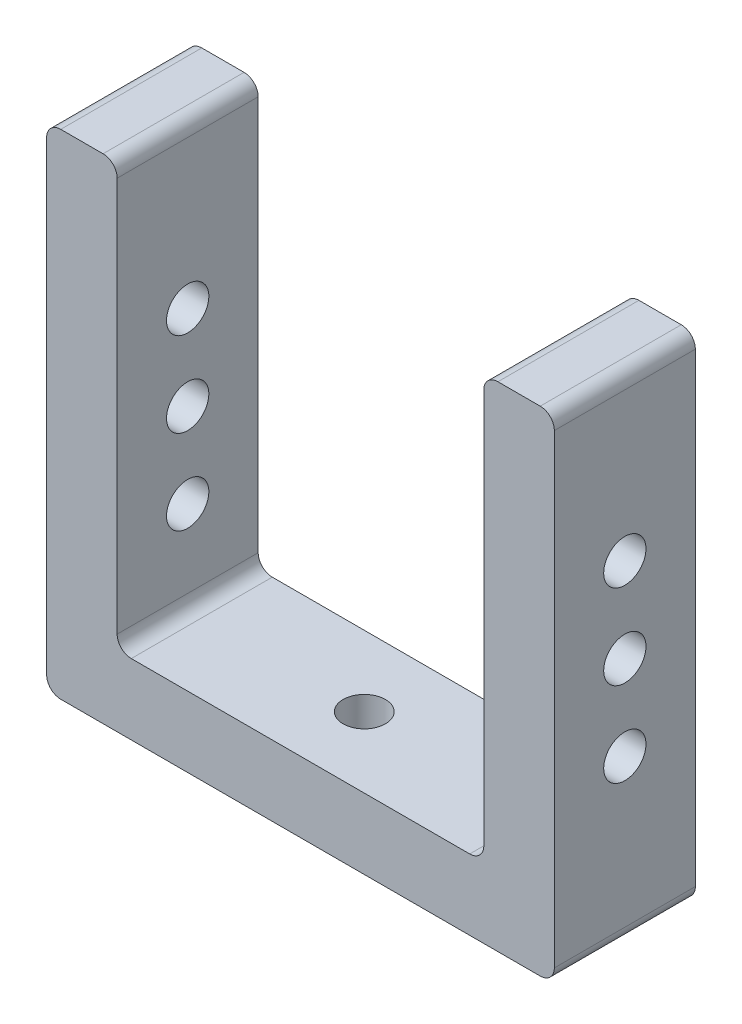
SolidWorks part; units mm, degrees
ref_plane "前视基准面" through (0, 0, 0) normal (0, 0, 1) x (1, 0, 0)
ref_plane "上视基准面" through (0, 0, 0) normal (0, 1, 0) x (1, 0, 0)
ref_plane "右视基准面" through (0, 0, 0) normal (1, 0, 0) x (0, 0, -1)
other "Configuration Table"
sketch "草图1" plane through (0, 0, 0) normal (0, 0, 1) x (1, 0, 0)
  line L0 (-17.0463, 30) -> (-12.0463, 30)
  line L1 (-12.0463, 30) -> (-12.0463, 1)
  line L2 (-11.0463, 0) -> (12.9537, 0)
  line L3 (13.9537, 1) -> (13.9537, 30)
  line L4 (13.9537, 30) -> (18.9537, 30)
  line L5 (18.9537, 30) -> (18.9537, -4)
  line L6 (12.9537, 0) -> (12.9537, -2)
  line L7 (17.9537, -5) -> (-16.0463, -5)
  line L8 (-17.0463, -4) -> (-17.0463, 30)
  arc A0 (18.9537, -4) -> (17.9537, -5) centre (17.9537, -4) cw
  arc A1 (12.9537, 0) -> (13.9537, 1) centre (12.9537, 1) ccw
  arc A2 (-16.0463, -5) -> (-17.0463, -4) centre (-16.0463, -4) cw
  arc A3 (-12.0463, 1) -> (-11.0463, 0) centre (-11.0463, 1) ccw
  point P17 (13.9537, 0)
  point P20 (-17.0463, -5)
  point P23 (-12.0463, 0)
  dimension "D1" = 1
  dimension "D2" = 26
  dimension "D3" = 5
  dimension "D4" = 35
  dimension "D5" = 30
  dimension "D6" = 30
  dimension "D7" = 5
extrude "凸台-拉伸1" add sketch "草图1" along normal blind 10 contours L8 L0 L1 A3 L2 A1 L3 L4 L5 A0 L7 A2
fillet "圆角1" radius 1 4 edges at (18.9537, 30, 5) (13.9537, 30, 5) (-17.0463, 30, 5) (-12.0463, 30, 5)
sketch "草图2" plane through (-17.0463, 0, 0) normal (-1, 0, 0) x (0, 0, 1)
  line L0 (0, 29) -> (0, -4) construction
  line L1 (0, 12.5) -> (10, 12.5) construction
  line L2 (10, -4) -> (10, 29) construction
  line L3 (5, 13) -> (5, -49987) construction
  circle A0 centre (5, 12.5) radius 1.5
  circle A1 centre (5, 6.5) radius 1.5
  circle A2 centre (5, 18.5) radius 1.5
  point P4 (0, 12.5)
  point P9 (5, 12.5)
  dimension "D1" = 3
  dimension "D2" = 2
  dimension "D3" = 2
sketch "草图3" plane through (0, -5, 0) normal (0, -1, 0) x (1, 0, 0)
  line L0 (0, 0) -> (0.9537, 10) construction
  line L1 (17.9537, 10) -> (-16.0463, 10) construction
  circle A0 centre (0.4768, 5) radius 1.5
  point P5 (0.4768, 5)
  dimension "D1" = 3
extrude "切除-拉伸2" cut sketch "草图3" against normal blind 6
extrude "切除-拉伸3" cut sketch "草图2" against normal through all
